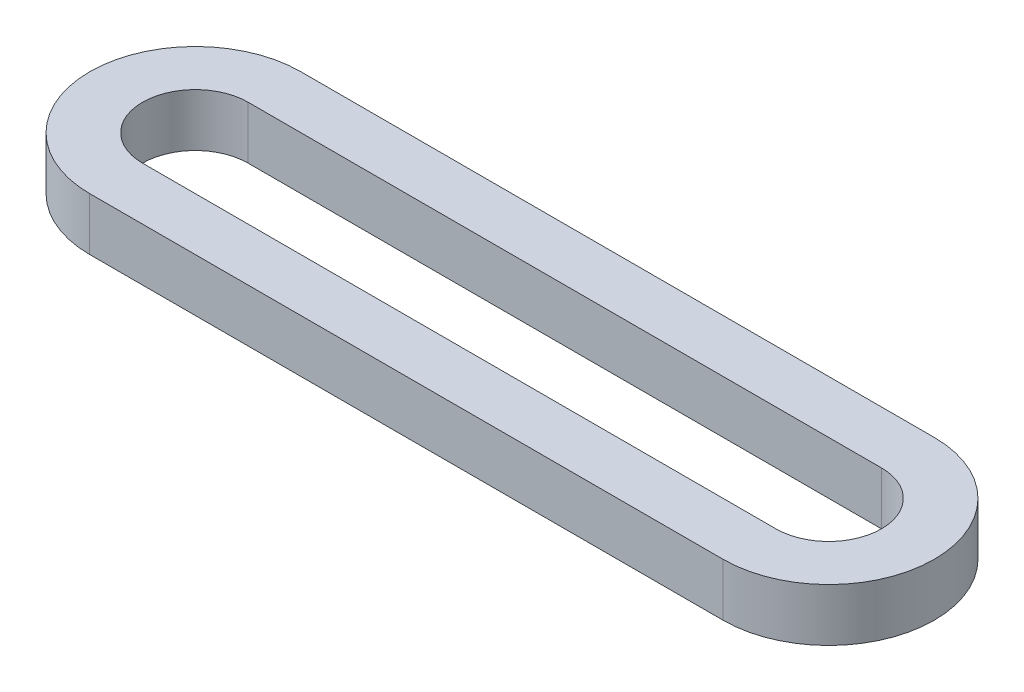
SolidWorks part; units mm, degrees
ref_plane "Front Plane" through (0, 0, 0) normal (0, 0, 1) x (1, 0, 0)
ref_plane "Top Plane" through (0, 0, 0) normal (0, 1, 0) x (1, 0, 0)
ref_plane "Right Plane" through (0, 0, 0) normal (1, 0, 0) x (0, 0, -1)
sketch "Sketch1" plane through (0, 0, 0) normal (0, 1, 0) x (1, 0, 0)
  line L0 (0, 0) -> (-38.1, 0) construction
  line L1 (0, -6.35) -> (-38.1, -6.35)
  line L2 (0, 6.35) -> (-38.1, 6.35)
  line L3 (0, 0) -> (-38.1, 0) construction
  line L4 (0, -3.175) -> (-38.1, -3.175)
  line L5 (0, 3.175) -> (-38.1, 3.175)
  arc A0 (0, -6.35) -> (0, 6.35) centre (0, 0) ccw
  arc A1 (-38.1, 6.35) -> (-38.1, -6.35) centre (-38.1, 0) ccw
  arc A2 (0, -3.175) -> (0, 3.175) centre (0, 0) ccw
  arc A3 (-38.1, 3.175) -> (-38.1, -3.175) centre (-38.1, 0) ccw
  point P3 (-19.05, 0)
  point P10 (-19.05, 0)
  point P15 (-38.1, 0)
  dimension "D2" = 3.175
  dimension "D3" = 6.35
  dimension "D1" = 38.1
extrude "Boss-Extrude1" add sketch "Sketch1" along normal blind 3.175
